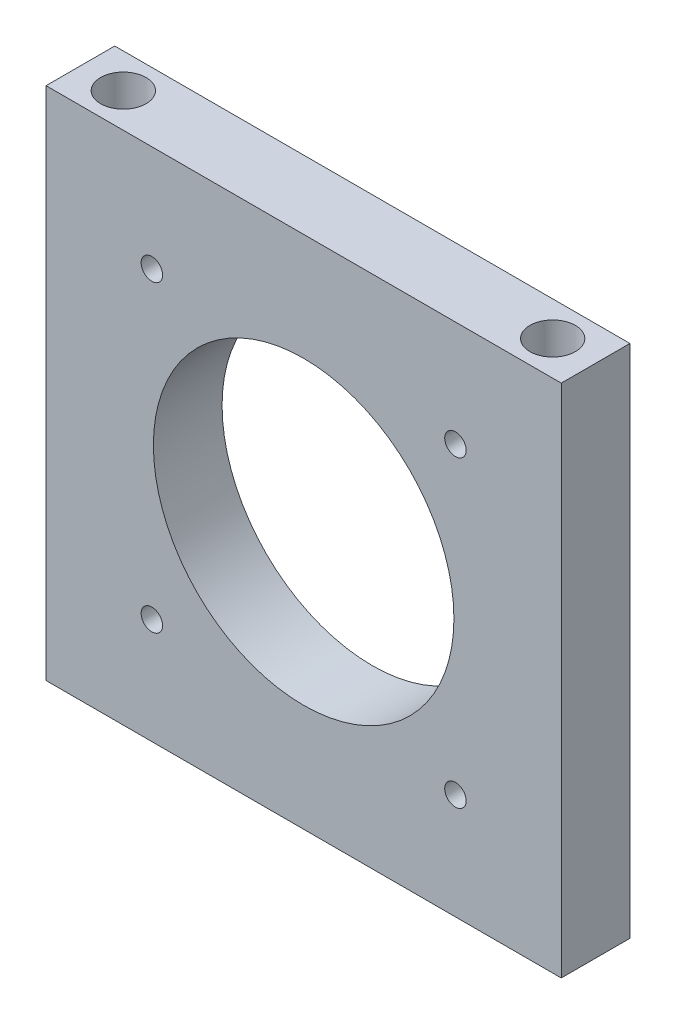
SolidWorks part; units mm, degrees
material "6061-T6 (SS)"
ref_plane "前基準面" through (0, 0, 0) normal (0, 0, 1) x (1, 0, 0)
ref_plane "上基準面" through (0, 0, 0) normal (0, 1, 0) x (1, 0, 0)
ref_plane "右基準面" through (0, 0, 0) normal (1, 0, 0) x (0, 0, -1)
sketch "草圖1" plane through (0, 0, 0) normal (0, 0, 1) x (1, 0, 0)
  line L1 (-30, -30) -> (30, -30)
  line L2 (-30, -30) -> (-30, 30)
  line L3 (-30, 30) -> (30, 30)
  line L4 (30, -30) -> (30, 30)
  line L5 (-30, -30) -> (30, 30) construction
  line L6 (-30, 30) -> (30, -30) construction
  point P0 (0, 0)
  dimension "D1" = 60
  dimension "D2" = 60
extrude "填料-伸長1" add sketch "草圖1" along normal mid plane 8
sketch "草圖2" plane through (0, 0, 4) normal (0, 0, 1) x (1, 0, 0)
  circle A0 centre (0, 0) radius 17.5
  dimension "D1" = 35
extrude "除料-伸長1" cut sketch "草圖2" against normal through all
hole_wizard "M3 螺紋孔1" positions "草圖3" profile "草圖4" tap size "M3" standard "ISO" end condition through all
sketch "草圖3" plane through (0, 0, 4) normal (0, 0, 1) x (1, 0, 0)
  line L1 (-17.6777, -17.6777) -> (17.6777, -17.6777) construction
  line L2 (-17.6777, -17.6777) -> (-17.6777, 17.6777) construction
  line L3 (-17.6777, 17.6777) -> (17.6777, 17.6777) construction
  line L4 (17.6777, -17.6777) -> (17.6777, 17.6777) construction
  line L5 (-17.6777, -17.6777) -> (17.6777, 17.6777) construction
  line L6 (-17.6777, 17.6777) -> (17.6777, -17.6777) construction
  circle A0 centre (0, 0) radius 25 construction
  point P5 (17.6777, 17.6777)
  point P162 (-17.6777, -17.6777)
  point P163 (-17.6777, 17.6777)
  point P164 (17.6777, -17.6777)
  dimension "D1" = 50
sketch "草圖4" plane through (17.6777, -17.6777, 4) normal (1, 0, 0) x (0, -1, 0)
  line L0 (0, 0) -> (0, 8)
  line L1 (0, 8) -> (1.25, 8)
  line L2 (1.25, 8) -> (1.25, 0)
  line L5 (1.25, 0) -> (0, 0)
  line L11 (0, -6.35) -> (0, 107.95) construction
  dimension "貫穿螺孔鑽直徑" = 2.5
  dimension "貫穿螺孔鑽深度" = 8
hole_wizard "M5 餘隙孔1" positions "草圖9" profile "草圖10" hole size "M5" standard "ISO" end condition through all
sketch "草圖9" plane through (0, 30, 0) normal (0, 1, 0) x (1, 0, 0)
  line L0 (-25, 0) -> (25, 0) construction
  point P2 (-25, 0)
  point P3 (25, 0)
  dimension "D1" = 50
sketch "草圖10" plane through (-25, 30, 0) normal (1, 0, 0) x (0, 0, 1)
  line L0 (0, 0) -> (0, 60)
  line L1 (0, 60) -> (2.65, 60)
  line L2 (2.65, 60) -> (2.65, 0)
  line L5 (2.65, 0) -> (0, 0)
  line L11 (0, -6.35) -> (0, 107.95) construction
  dimension "貫穿孔直徑" = 5.3
  dimension "貫穿孔深度" = 60
